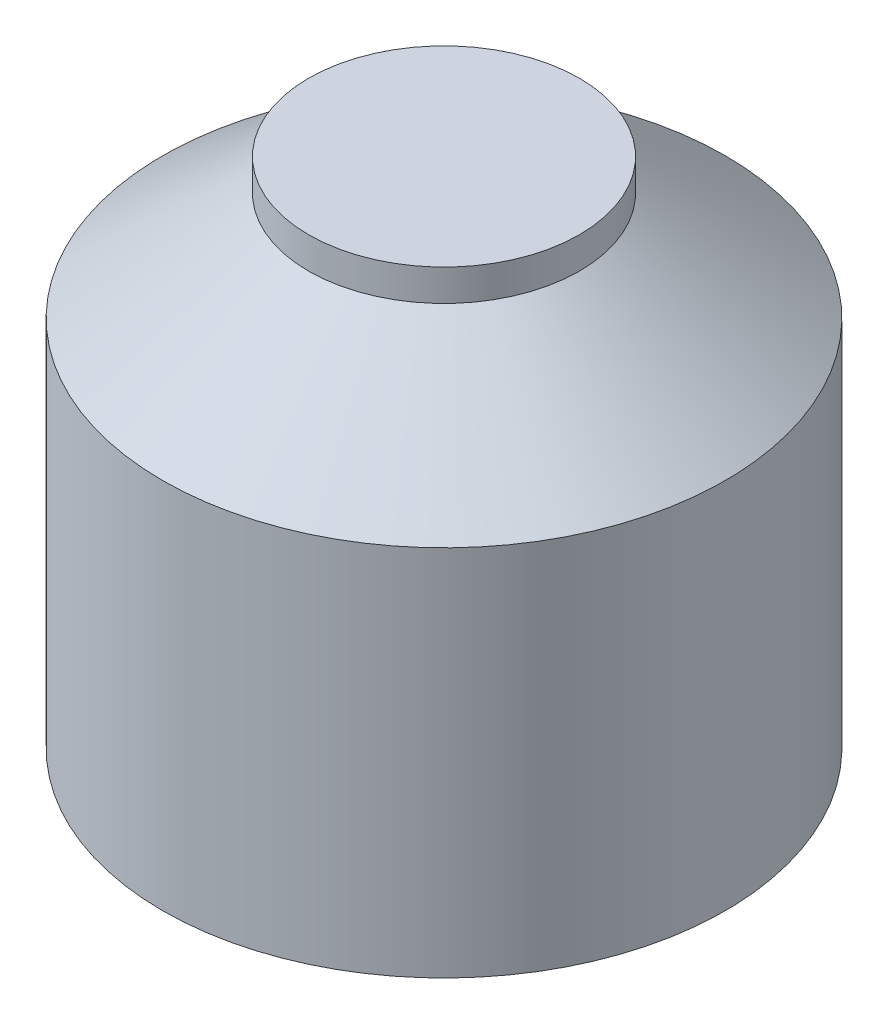
SolidWorks part; units mm, degrees
ref_plane "Front Plane" through (0, 0, 0) normal (0, 0, 1) x (1, 0, 0)
ref_plane "Top Plane" through (0, 0, 0) normal (0, 1, 0) x (1, 0, 0)
ref_plane "Right Plane" through (0, 0, 0) normal (1, 0, 0) x (0, 0, -1)
sketch "Sketch1" plane through (0, 0, 0) normal (0, 0, 1) x (1, 0, 0)
  line L0 (0, 0) -> (41.529, 0) construction
  line L1 (41.529, 0) -> (41.529, 55)
  line L2 (41.529, 55) -> (20, 71.0096)
  line L3 (20, 71.0096) -> (20, 75.666)
  line L4 (20, 75.666) -> (0, 75.666)
  line L5 (0, 75.666) -> (0, 0) construction
  line L6 (37.529, 0) -> (37.529, 52.9898)
  line L7 (37.529, 52.9898) -> (18.8208, 66.9017)
  line L8 (18.8208, 66.9017) -> (18.8208, 73.945)
  line L9 (18.8208, 73.945) -> (0, 73.945)
  line L10 (37.529, 0) -> (41.529, 0)
  line L11 (0, 75.666) -> (0, 73.945)
  dimension "D1" = 75.666
  dimension "D2" = 55
  dimension "D3" = 4
  dimension "D4" = 4
  dimension "D5" = 41.529
  dimension "D6" = 20
revolve "Revolve1" add sketch "Sketch1" angle 360 about L5
